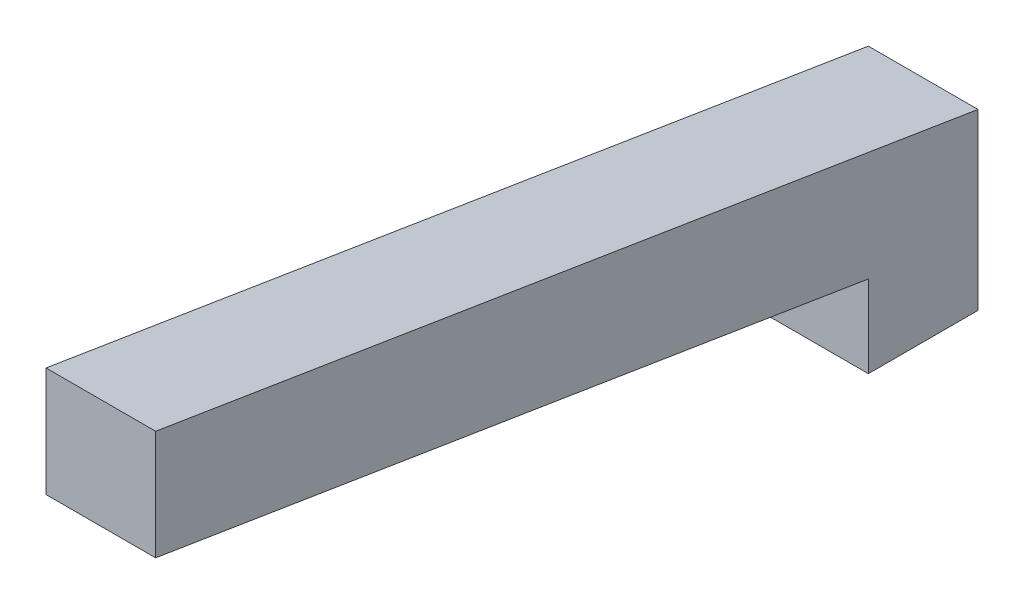
SolidWorks part; units mm, degrees
ref_plane "Front Plane" through (0, 0, 0) normal (0, 0, 1) x (1, 0, 0)
ref_plane "Top Plane" through (0, 0, 0) normal (0, 1, 0) x (1, 0, 0)
ref_plane "Right Plane" through (0, 0, 0) normal (1, 0, 0) x (0, 0, -1)
sketch "Sketch2" plane through (0, 0, 0) normal (1, 0, 0) x (0, 0, -1)
  line L0 (0, 0) -> (5.08, 0)
  line L1 (5.08, 0) -> (5.08, 8.0635)
  line L2 (5.08, 8.0635) -> (-33.02, 14.2004)
  line L3 (-33.02, 14.2004) -> (-33.02, 9.1204)
  line L4 (-33.02, 9.1204) -> (0, 3.8018)
  line L5 (0, 3.8018) -> (0, 0)
  point P7 (-27.1463, 12.4222)
  point P8 (-33.02, 14.2004)
  dimension "D1" = 5.08
  dimension "D2" = 5.08
  dimension "D3" = 38.1
extrude "Boss-Extrude1" add sketch "Sketch2" along normal blind 5.08
